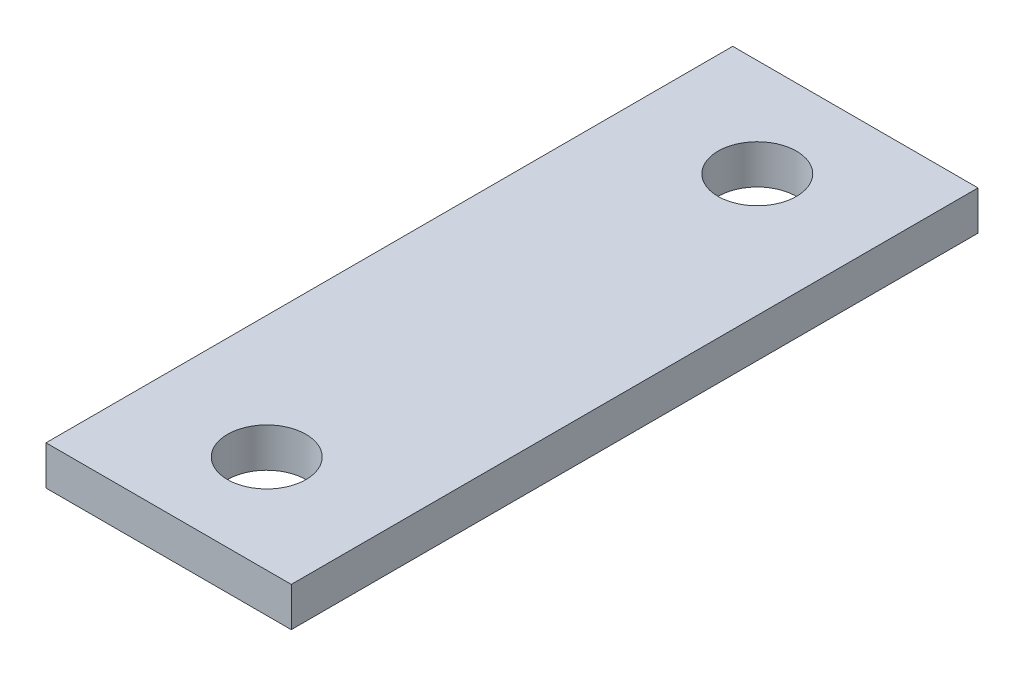
SolidWorks part; units mm, degrees
ref_plane "Front Plane" through (0, 0, 0) normal (0, 0, 1) x (1, 0, 0)
ref_plane "Top Plane" through (0, 0, 0) normal (0, 1, 0) x (1, 0, 0)
ref_plane "Right Plane" through (0, 0, 0) normal (1, 0, 0) x (0, 0, -1)
sketch "Sketch1" plane through (0, 0, 0) normal (0, 1, 0) x (1, 0, 0)
  line L1 (0, 0) -> (25, 0)
  line L2 (0, 0) -> (0, 70)
  line L3 (0, 70) -> (25, 70)
  line L4 (25, 0) -> (25, 70)
  dimension "D1" = 25
  dimension "D2" = 70
extrude "Boss-Extrude1" add sketch "Sketch1" along normal blind 4
sketch "Sketch2" plane through (0, 4, 0) normal (0, 1, 0) x (1, 0, 0)
  line L0 (25, 70) -> (0, 70) construction
  line L2 (0, 70) -> (0, 0) construction
  line L3 (25, 0) -> (25, 70) construction
  line L4 (0, 0) -> (25, 0) construction
  circle A0 centre (12.5, 60) radius 4
  circle A2 centre (12.5, 10) radius 4
  dimension "D2" = 8
  dimension "D4" = 8
  dimension "D5" = 10
  dimension "D6" = 12.5
  dimension "D9" = 12.5
  dimension "D10" = 10
extrude "Cut-Extrude1" cut sketch "Sketch2" against normal through all
